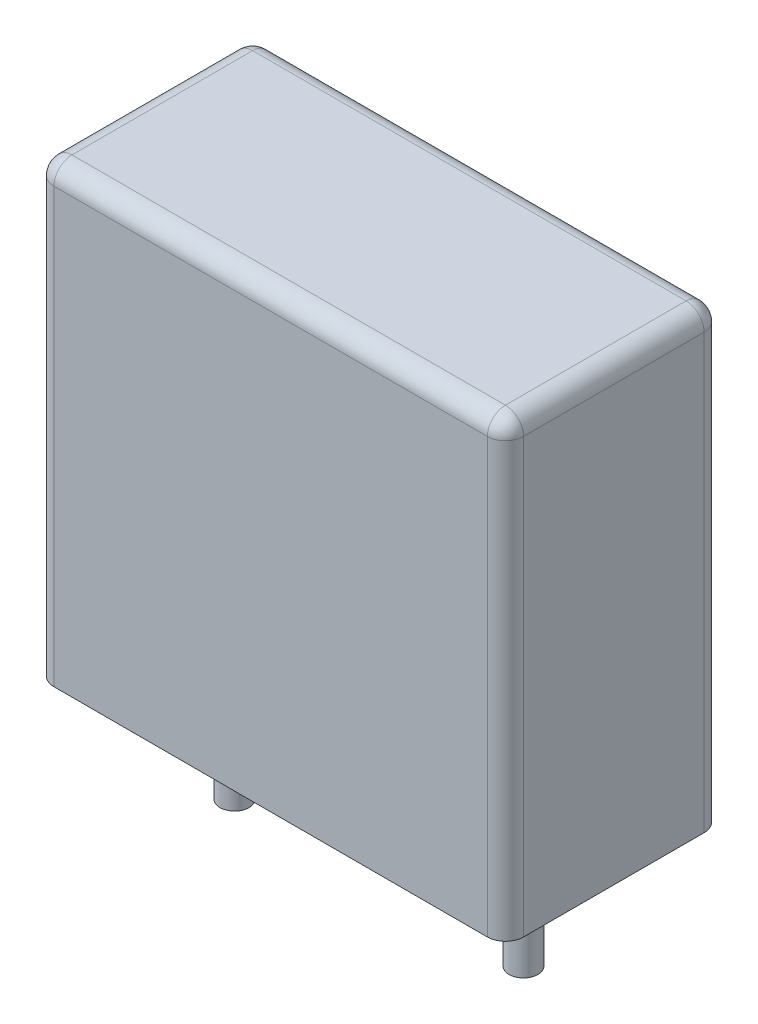
SolidWorks part; units mm, degrees
ref_plane "Спереди" through (0, 0, 0) normal (0, 0, 1) x (1, 0, 0)
ref_plane "Сверху" through (0, 0, 0) normal (0, 1, 0) x (1, 0, 0)
ref_plane "Справа" through (0, 0, 0) normal (1, 0, 0) x (0, 0, -1)
sketch "Эскиз2" plane through (0, 0, 0) normal (0, 1, 0) x (1, 0, 0)
  line L1 (-6.5, -3) -> (6.5, -3)
  line L2 (-6.5, -3) -> (-6.5, 3)
  line L3 (-6.5, 3) -> (6.5, 3)
  line L4 (6.5, -3) -> (6.5, 3)
  line L5 (-6.5, -3) -> (6.5, 3) construction
  line L6 (-6.5, 3) -> (6.5, -3) construction
  point P0 (0, 0)
  dimension "D1" = 13
  dimension "D2" = 6
extrude "Бобышка-Вытянуть1" add sketch "Эскиз2" along normal blind 12.5
sketch "Эскиз3" plane through (0, 0, 0) normal (0, -1, 0) x (1, 0, 0)
  line L0 (-4, 0) -> (4, 0) construction
  circle A0 centre (-4, 0) radius 0.4
  circle A1 centre (4, 0) radius 0.4
  point P4 (0, 0)
  dimension "D1" = 0.8
  dimension "D2" = 8
extrude "Бобышка-Вытянуть2" add sketch "Эскиз3" along normal blind 3.2
fillet "Скругление1" radius 0.5 8 edges at (0, 12.5, 3) (-6.5, 12.5, 0) (0, 12.5, -3) (6.5, 12.5, 0) (-6.5, 6.25, -3) (6.5, 6.25, -3) (6.5, 6.25, 3) (-6.5, 6.25, 3)
